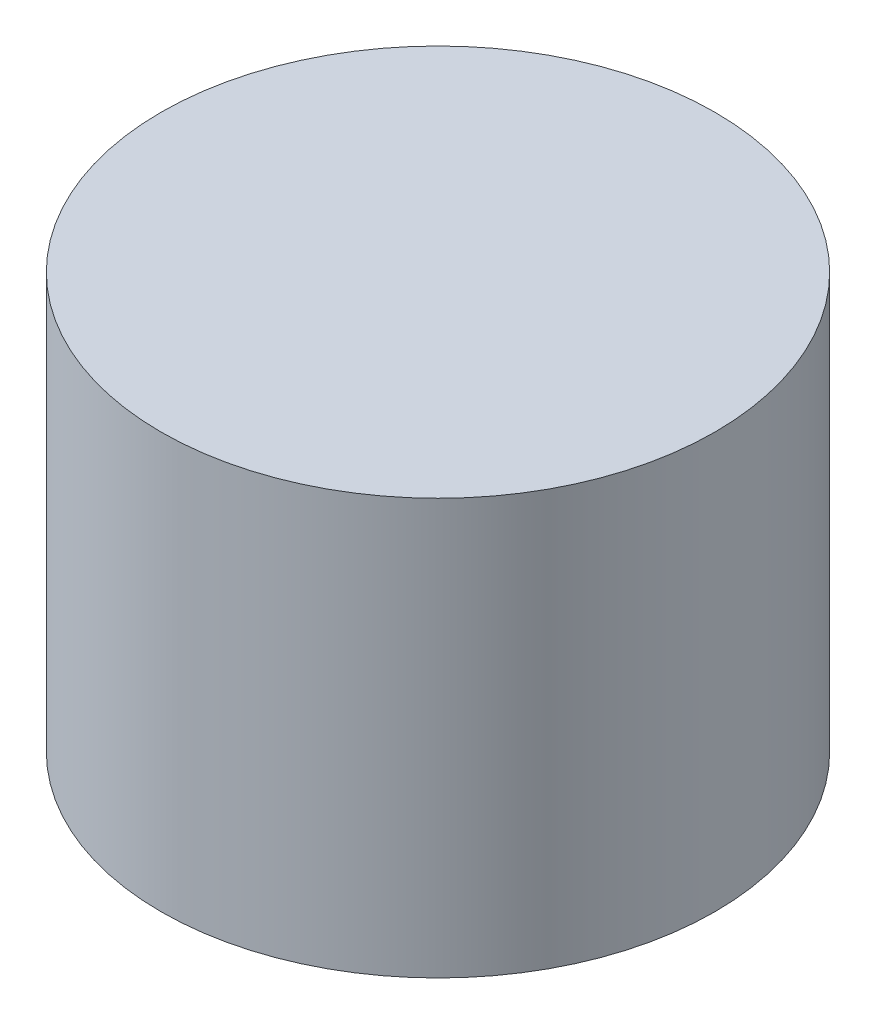
SolidWorks part; units mm, degrees
ref_plane "前视基准面" through (0, 0, 0) normal (0, 0, 1) x (1, 0, 0)
ref_plane "上视基准面" through (0, 0, 0) normal (0, 1, 0) x (1, 0, 0)
ref_plane "右视基准面" through (0, 0, 0) normal (1, 0, 0) x (0, 0, -1)
sketch "草图2" plane through (0, 0, 0) normal (0, 1, 0) x (1, 0, 0)
  line L0 (-10, 0) -> (10, 0) construction
  line L1 (0, 10) -> (0, -10) construction
  circle A0 centre (0, 0) radius 10
  circle A1 centre (0, 0) radius 4
  dimension "D1" = 20
  dimension "D2" = 8
extrude "凸台-拉伸1" add sketch "草图2" along normal blind 15 contours A0
